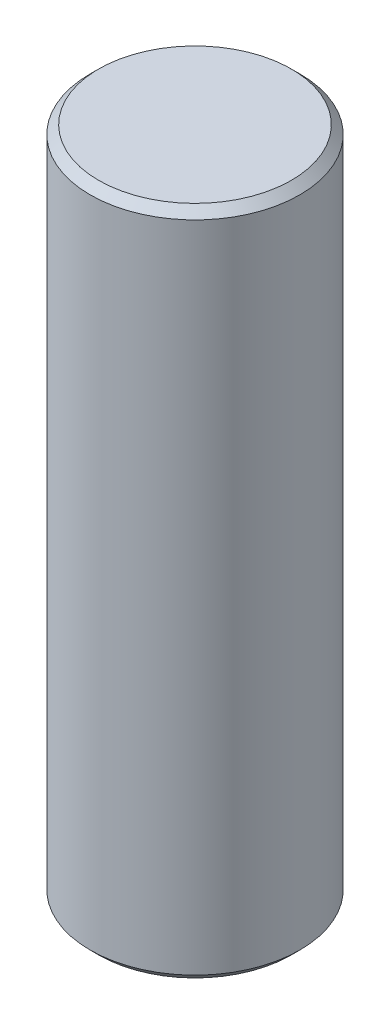
SolidWorks part; units mm, degrees
material "201 Annealed Stainless Steel (SS)"
ref_plane "Front Plane" through (0, 0, 0) normal (0, 0, 1) x (1, 0, 0)
ref_plane "Top Plane" through (0, 0, 0) normal (0, 1, 0) x (1, 0, 0)
ref_plane "Right Plane" through (0, 0, 0) normal (1, 0, 0) x (0, 0, -1)
sketch "Sketch1" plane through (0, 0, 0) normal (0, 1, 0) x (1, 0, 0)
  circle A0 centre (0, 0) radius 2.5
  dimension "D1" = 5
extrude "Boss-Extrude1" add sketch "Sketch1" along normal blind 16
chamfer "Chamfer1" distance 0.2 angle 45 2 edges at (0, 0, 2.5) (0, 16, 2.5)
ref_plane "Plane1" through (0, 8, 0) normal (0, 1, 0) x (1, 0, 0)
